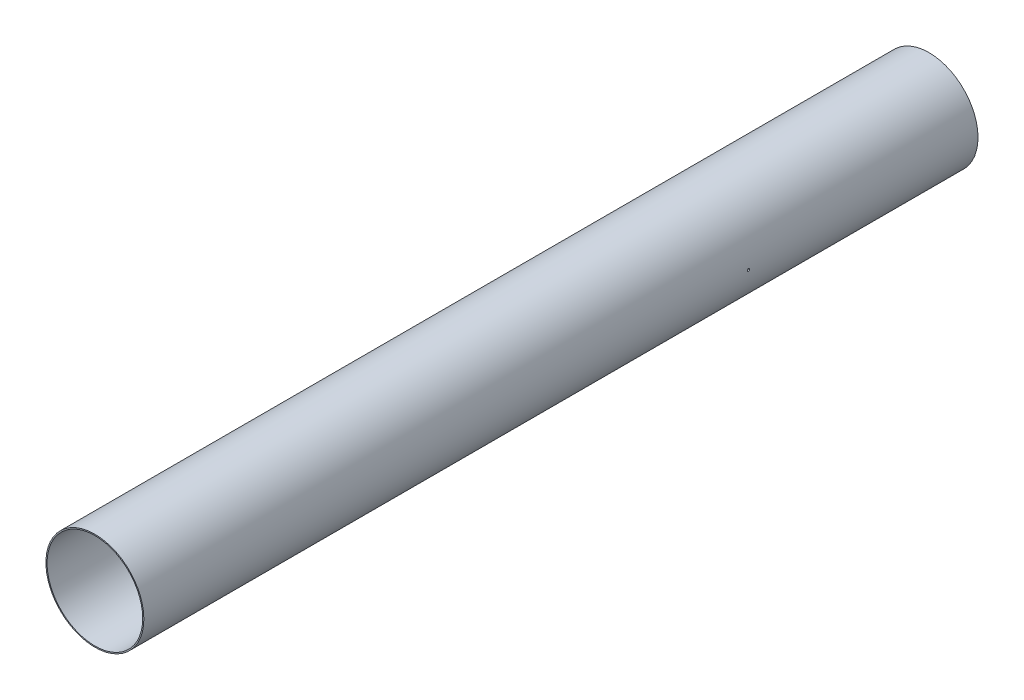
SolidWorks part; units mm, degrees
material "PVC Rigid"
ref_plane "Front Plane" through (0, 0, 0) normal (0, 0, 1) x (1, 0, 0)
ref_plane "Top Plane" through (0, 0, 0) normal (0, 1, 0) x (1, 0, 0)
ref_plane "Right Plane" through (0, 0, 0) normal (1, 0, 0) x (0, 0, -1)
sketch "Sketch1" plane through (0, 0, 0) normal (0, 0, 1) x (1, 0, 0)
  circle A0 centre (0, 0) radius 62.5
  circle A1 centre (0, 0) radius 64
  dimension "D1" = 125
  dimension "D2" = 128
extrude "Boss-Extrude1" add sketch "Sketch1" along normal mid plane 1090
sketch "Sketch2" plane through (0, 0, 0) normal (1, 0, 0) x (0, 0, -1)
  line L1 (545, -64) -> (545, 64) construction
  circle A0 centre (245, 0) radius 1.5
  dimension "D1" = 300
  dimension "D2" = 3
extrude "Cut-Extrude1" cut sketch "Sketch2" along normal through all
